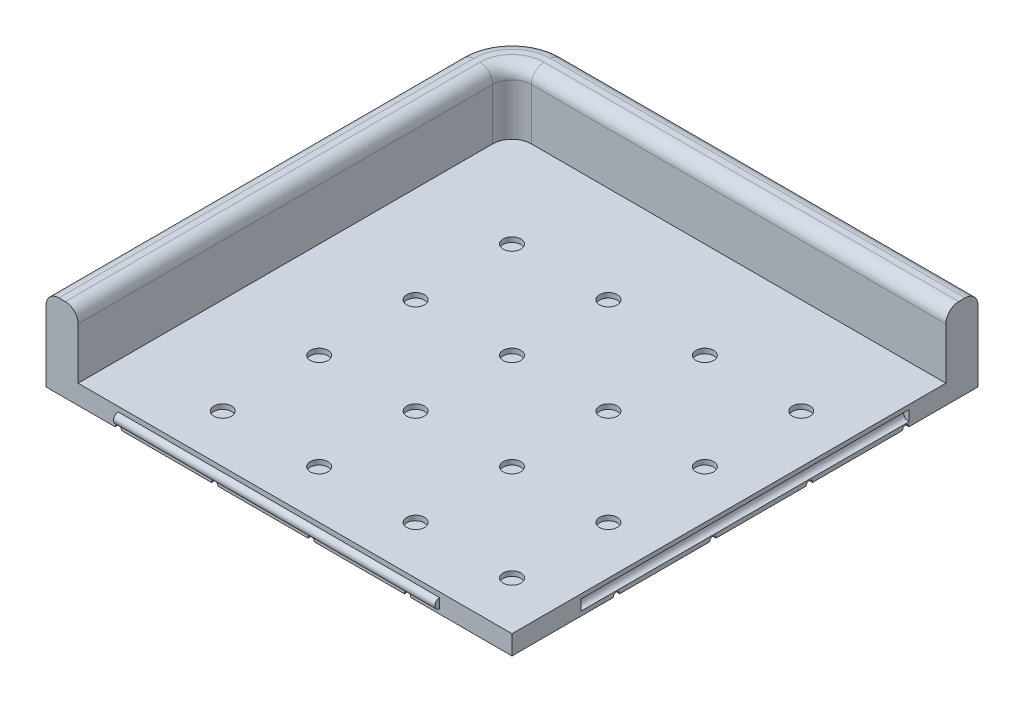
SolidWorks part; units mm, degrees
material "ABS"
ref_plane "Front Plane" through (0, 0, 0) normal (0, 0, 1) x (1, 0, 0)
ref_plane "Top Plane" through (0, 0, 0) normal (0, 1, 0) x (1, 0, 0)
ref_plane "Right Plane" through (0, 0, 0) normal (1, 0, 0) x (0, 0, -1)
sketch "Sketch1" plane through (0, 0, 0) normal (0, 1, 0) x (1, 0, 0)
  line L1 (-56.5, 72.5) -> (72.5, 72.5)
  line L2 (-72.5, 56.5) -> (-72.5, -72.5)
  line L3 (-72.5, -72.5) -> (72.5, -72.5)
  line L4 (72.5, 72.5) -> (72.5, -72.5)
  line L5 (-72.5, 72.5) -> (72.5, -72.5) construction
  line L6 (-72.5, -72.5) -> (72.5, 72.5) construction
  arc A0 (-56.5, 72.5) -> (-72.5, 56.5) centre (-56.5, 56.5) ccw
  point P0 (0, 0)
  dimension "D2" = 16
  dimension "D1" = 145
extrude "Boss-Extrude1" add sketch "Sketch1" along normal blind 6
sketch "Sketch2" plane through (0, 6, 0) normal (0, 1, 0) x (1, 0, 0)
  line L0 (-72.5, -72.5) -> (-72.5, 56.5)
  line L1 (-56.5, 72.5) -> (72.5, 72.5)
  arc A0 (-72.5, 56.5) -> (-56.5, 72.5) centre (-56.5, 56.5) cw
  arc A1 (-56.5, 72.5) -> (-72.5, 56.5) centre (-56.5, 56.5) ccw construction
extrude "Extrude-Thin1" add sketch "Sketch2" along normal blind 20 thin
sketch "Sketch3" plane through (0, 6, 0) normal (0, 1, 0) x (1, 0, 0)
  line L0 (72.5, -72.5) -> (72.5, 62.5) construction
  line L1 (-62.5, -72.5) -> (72.5, -72.5) construction
  circle A0 centre (57.5, -57.5) radius 2.75
  dimension "D1" = 5.5
  dimension "D2" = 15
  dimension "D3" = 15
extrude "Cut-Extrude1" cut sketch "Sketch3" against normal blind 1.5
pattern_linear "LPattern1" count 4 spacing 30 along (-1, 0, 0) count 4 spacing 30 along (0, 0, -1) of "Cut-Extrude1"
fillet "Fillet1" radius 4 6 edges at (8, 26, -72.5) (-67.8137, 26, -67.8137) (-72.5, 26, 8) (8, 26, -62.5) (-62.5, 26, 8) (-60.7426, 26, -60.7426)
sketch "Sketch4" plane through (0, 0, 0) normal (1, 0, 0) x (0, 0, -1)
  line L0 (-72.5, 6) -> (-72.5, 0) construction
  circle A0 centre (-72.5, 3) radius 1.5
  point P2 (0, 0)
  point P5 (-72.5, 3)
  dimension "D1" = 3
extrude "Boss-Extrude2" add sketch "Sketch4" along normal mid plane 100
sketch "Sketch5" plane through (0, 0, 0) normal (0, 0, 1) x (1, 0, 0)
  line L0 (72.5, 6) -> (72.5, 0) construction
  circle A0 centre (72.5, 3) radius 1.65
  point P4 (72.5, 3)
  dimension "D1" = 3.3
extrude "Cut-Extrude2" cut sketch "Sketch5" against normal mid plane 102
sketch "Sketch6" plane through (0, 0, 0) normal (0, 0, 1) x (1, 0, 0)
  circle A0 centre (-50, 0) radius 1
  dimension "D1" = 2
extrude "Cut-Extrude3" cut sketch "Sketch6" against normal through all both and the other way through all
pattern_linear "LPattern2" count 4 spacing 30 along (1, 0, 0) of "Cut-Extrude3"
sketch "Sketch7" plane through (0, 0, 0) normal (1, 0, 0) x (0, 0, -1)
  circle A0 centre (50, 0) radius 1
extrude "Cut-Extrude4" cut sketch "Sketch7" against normal through all both and the other way through all
pattern_linear "LPattern3" count 4 spacing 30 along (0, 0, 1) of "Cut-Extrude4"
